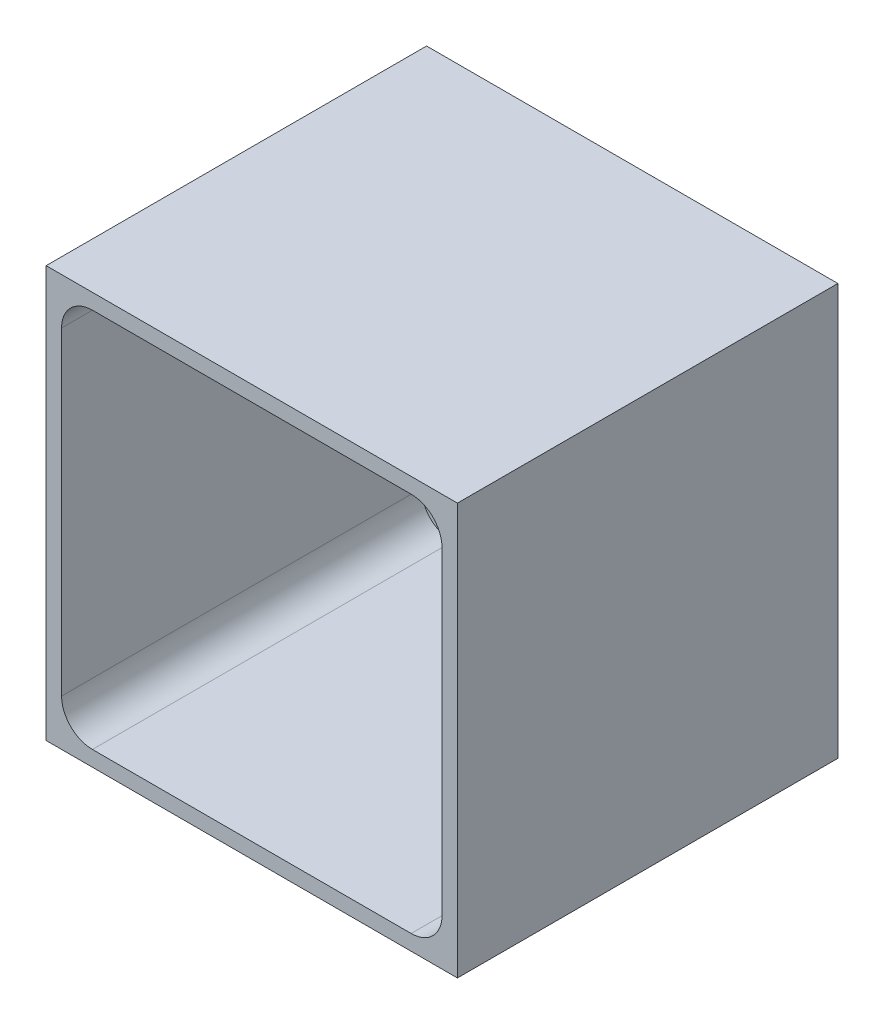
SolidWorks part; units mm, degrees
ref_plane "Front Plane" through (0, 0, 0) normal (1, 0, 0) x (0, 1, 0)
ref_plane "Top Plane" through (0, 0, 0) normal (0, 0, 1) x (0, 1, 0)
ref_plane "Right Plane" through (0, 0, 0) normal (0, 1, 0) x (-1, 0, 0)
sketch "Sketch1" plane through (0, 0, 0) normal (0, 0, 1) x (0, 1, 0)
  line L1 (-18.5, -18.5) -> (18.5, -18.5)
  line L2 (-18.5, -18.5) -> (-18.5, 18.5)
  line L3 (-18.5, 18.5) -> (18.5, 18.5)
  line L4 (18.5, -18.5) -> (18.5, 18.5)
  line L5 (-18.5, -18.5) -> (18.5, 18.5) construction
  line L6 (-18.5, 18.5) -> (18.5, -18.5) construction
  line L7 (-20, -20) -> (20, -20)
  line L8 (-20, -20) -> (-20, 20)
  line L9 (-20, 20) -> (20, 20)
  line L10 (20, -20) -> (20, 20)
  line L11 (-20, -20) -> (20, 20) construction
  line L12 (-20, 20) -> (20, -20) construction
  point P0 (0, 0)
  point P6 (0, 0)
  dimension "D1" = 37
  dimension "D2" = 37
  dimension "D3" = 40
  dimension "D4" = 40
extrude "Boss-Extrude1" add sketch "Sketch1" along normal blind 35
sketch "Sketch2" plane through (0, 0, 0) normal (0, 0, -1) x (1, 0, 0)
  line L20 (-20, -20) -> (20, -20)
  line L21 (20, -20) -> (20, 20)
  line L22 (20, 20) -> (-20, 20)
  line L23 (-20, 20) -> (-20, -20)
  line L24 (-20, -20) -> (20, -20)
  line L25 (20, -20) -> (20, 20)
  line L26 (20, 20) -> (-20, 20)
  line L27 (-20, 20) -> (-20, -20)
  dimension "D1" = 0
extrude "Boss-Extrude2" add sketch "Sketch2" along normal blind 2
fillet "Fillet1" radius 3 4 edges at (-18.5, 18.5, 17.5) (18.5, 18.5, 17.5) (-18.5, -18.5, 17.5) (18.5, -18.5, 17.5)
